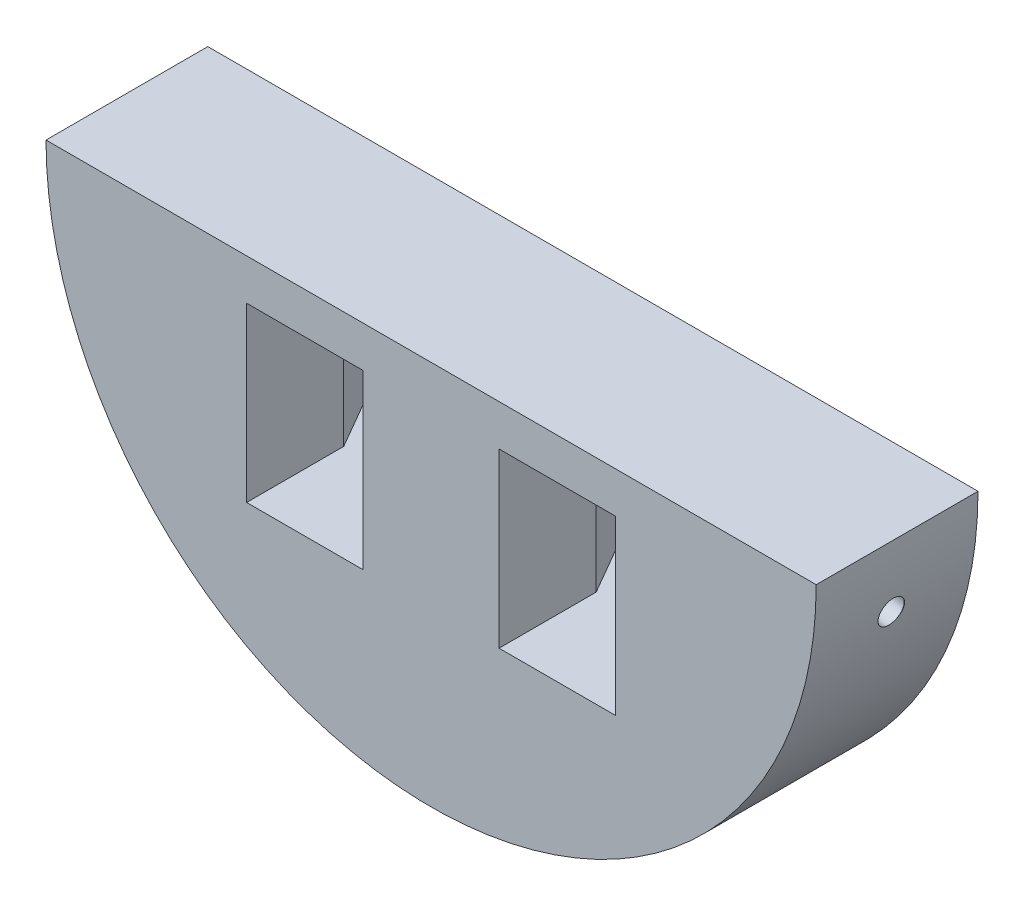
SolidWorks part; units mm, degrees
ref_plane "Front Plane" through (0, 0, 0) normal (0, 0, 1) x (1, 0, 0)
ref_plane "Top Plane" through (0, 0, 0) normal (0, 1, 0) x (1, 0, 0)
ref_plane "Right Plane" through (0, 0, 0) normal (1, 0, 0) x (0, 0, -1)
sketch "Sketch1" plane through (0, 0, 0) normal (0, 0, 1) x (1, 0, 0)
  line L0 (-119, 0) -> (0, 0)
  line L3 (-49, -33) -> (-31, -33)
  line L4 (-49, -33) -> (-49, -15)
  line L5 (-49, -15) -> (-31, -15)
  line L6 (-31, -33) -> (-31, -15)
  line L7 (-88, -33) -> (-70, -33)
  line L8 (-88, -33) -> (-88, -15)
  line L9 (-88, -15) -> (-70, -15)
  line L10 (-70, -33) -> (-70, -15)
  arc A1 (-119, 0) -> (0, 0) centre (-59.5, 0) ccw
  point P0 (-79, -15)
  point P13 (-40, -15)
  dimension "D1" = 19.5
  dimension "D7" = 59.5
  dimension "D2" = 15
  dimension "D4" = 18
  dimension "D5" = 19.5
extrude "Boss-Extrude1" add sketch "Sketch1" along normal blind 25
hole_wizard "Ø4.0mm Dowel Hole2" positions "3DSketch2" profile "Sketch4" hole size "Ø4.0" standard "ANSI Metric"
sketch3d "3DSketch2"
  line L2 (0, 0, 25) -> (0, 0, 0) construction
  line L4 (0, 0, 25) -> (0, 0, 0) construction
  line L5 (0, 0, 12.5) -> (-0.9039, -10.3321, 12.5) construction
  line L8 (-59.5, 0, 0) -> (-59.5, 0, 25) construction
  line L9 (0, 0, 0) -> (-119, 0, 0) construction
  line L10 (0, 0, 25) -> (-119, 0, 25) construction
  line L12 (-59.5, 0, 12.5) -> (-0.9039, -10.3321, 12.5) construction
  line L16 (-59.5, 0, 12.5) -> (0, 0, 12.5) construction
  point P0 (-0.9039, -10.3321, 12.5)
  point P16 (-0.9039, -10.3321, 12.5)
  point P23 (-0.9039, -10.3321, 12.5)
  point P25 (-0.9039, -10.3321, 12.5)
  dimension "D1" = 10
sketch "Sketch4" plane through (-0.9039, -10.3321, 12.5) normal (0, 0, 1) x (0.1736, 0.9848, 0)
  line L0 (0, 0) -> (0, 11.2017)
  line L1 (0, 11.2017) -> (2, 10)
  line L2 (2, 10) -> (2, 0.025)
  line L3 (2, 0.025) -> (2.025, 0)
  line L5 (2.025, 0) -> (0, 0)
  line L6 (-2, 0.025) -> (-2.025, 0) construction
  line L10 (0, 11.2017) -> (-2, 10) construction
  line L11 (0, -6.35) -> (0, 107.95) construction
  dimension "Hole Dia." = 4
  dimension "Hole Depth" = 10
  dimension "Near C'Sink Dia." = 4.05
  dimension "Near C'Sink Angle" = 90
  dimension "Drill Angle" = 118
pattern_circular "CirPattern1" count 5 over 160 about axis through (-59.5, 0, 0) along (0, 0, 1) of "Ø4.0mm Dowel Hole2"
chamfer "Chamfer1" distance 15 angle 30 2 edges at (-79, -15, 25) (-40, -15, 25)
chamfer "Chamfer2" distance 10 angle 30 4 edges at (-49, -24, 0) (-31, -24, 0) (-88, -24, 0) (-70, -24, 0)
chamfer "Chamfer3" distance 4 angle 60 2 edges at (-79, -15, 0) (-40, -15, 0)
